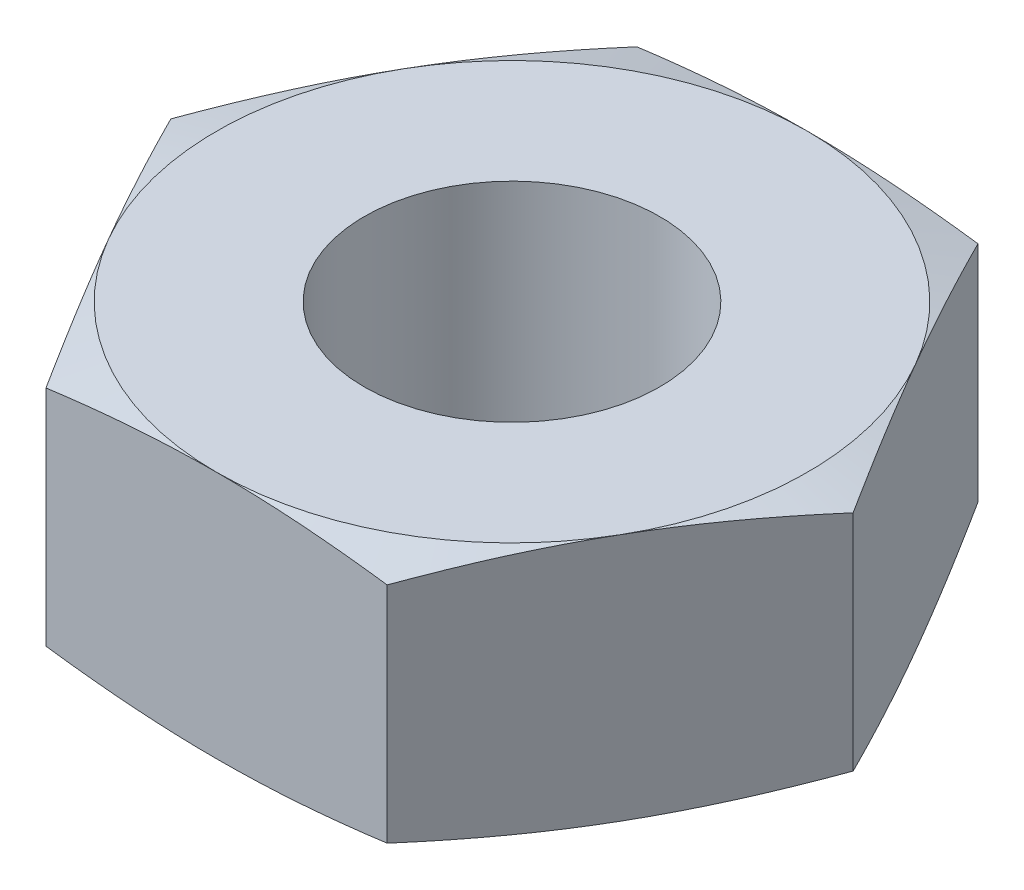
SolidWorks part; units mm, degrees
ref_plane "前视基准面" through (0, 0, 0) normal (0, 0, 1) x (1, 0, 0)
ref_plane "上视基准面" through (0, 0, 0) normal (0, 1, 0) x (1, 0, 0)
ref_plane "右视基准面" through (0, 0, 0) normal (1, 0, 0) x (0, 0, -1)
other "Configuration Table"
sketch "草图1" plane through (0, 0, 0) normal (0, 1, 0) x (1, 0, 0)
  line L1 (2.8868, 0) -> (1.4434, 2.5)
  line L2 (1.4434, 2.5) -> (-1.4434, 2.5)
  line L3 (-1.4434, 2.5) -> (-2.8868, 0)
  line L4 (-2.8868, 0) -> (-1.4434, -2.5)
  line L5 (-1.4434, -2.5) -> (1.4434, -2.5)
  line L6 (1.4434, -2.5) -> (2.8868, 0)
  circle A0 centre (0, 0) radius 2.5 construction
  dimension "D1" = 5
extrude "凸台-拉伸1" add sketch "草图1" along normal blind 2.1
hole_wizard "M3 螺纹孔1" positions "草图2" profile "草图3" tap size "M3" standard "GB" end condition through all
sketch "草图2" plane through (0, 2.1, 0) normal (0, 1, 0) x (1, 0, 0)
  point P0 (0, 0)
sketch "草图3" plane through (0, 2.1, 0) normal (1, 0, 0) x (0, 0, 1)
  line L0 (0, 0) -> (0, 2.1)
  line L1 (0, 2.1) -> (1.25, 2.1)
  line L2 (1.25, 2.1) -> (1.25, 0)
  line L5 (1.25, 0) -> (0, 0)
  line L11 (0, -6.35) -> (0, 107.95) construction
  dimension "通孔螺纹孔钻头直径" = 2.5
  dimension "通孔螺纹孔钻头深度" = 2.1
cosmetic thread "孔螺纹线1" parameters "D2"=3
sketch "草图5" plane through (0, 0, 0) normal (1, 0, 0) x (0, 0, -1)
  line L0 (0, 0) -> (0, -50000) construction
  line L1 (-3.5, 1.05) -> (49996.5, 1.05) construction
  line L2 (-2.5, 2.1) -> (-2.5, 0) construction
  line L3 (-2.5, 0) -> (-4.3201, 0.4877)
  line L4 (-4.3201, 0.4877) -> (-4.3201, -0.8558)
  line L5 (-4.3201, -0.8558) -> (-2.5, 0)
  line L6 (-4.3201, 2.9558) -> (-2.5, 2.1)
  line L7 (-4.3201, 1.6123) -> (-4.3201, 2.9558)
  line L8 (-2.5, 2.1) -> (-4.3201, 1.6123)
  point P7 (-2.5, 1.05)
  dimension "D1" = 75
revolve "切除-旋转1" cut sketch "草图5" angle 360 about L0
